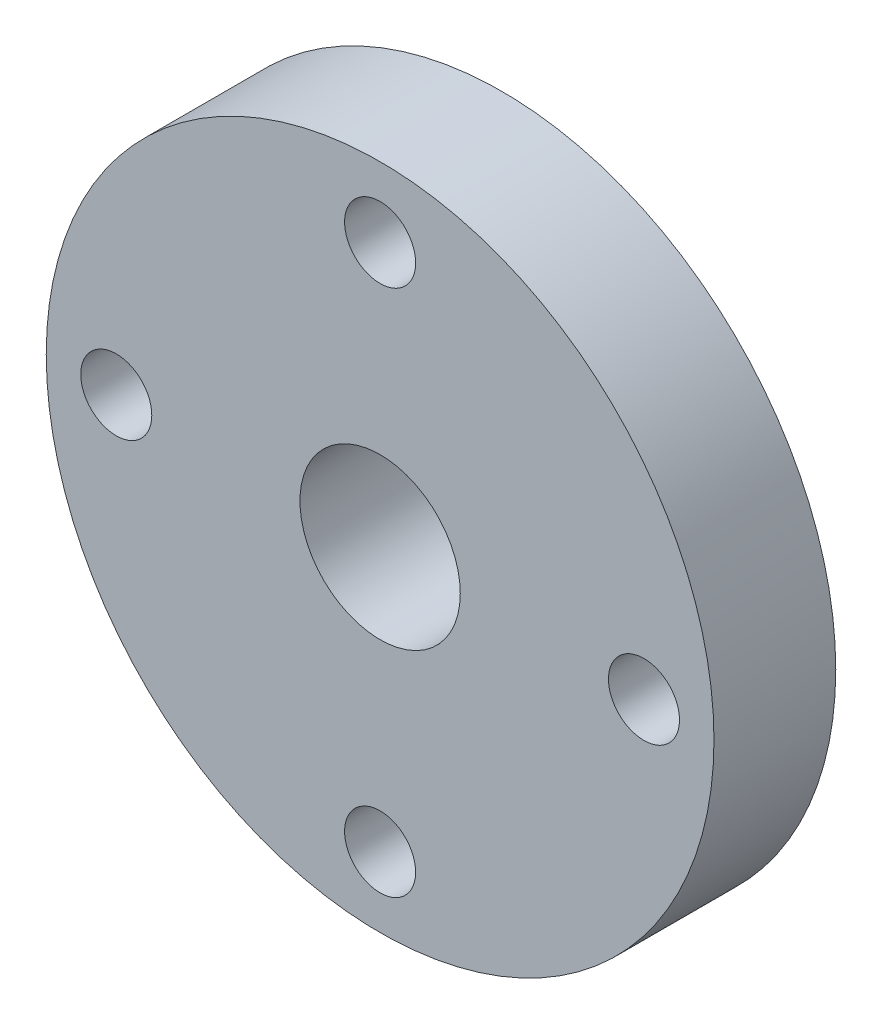
SolidWorks part; units mm, degrees
material "Balsa"
ref_plane "Front Plane" through (0, 0, 0) normal (0, 0, 1) x (1, 0, 0)
ref_plane "Top Plane" through (0, 0, 0) normal (0, 1, 0) x (1, 0, 0)
ref_plane "Right Plane" through (0, 0, 0) normal (1, 0, 0) x (0, 0, -1)
sketch "Sketch1" plane through (0, 0, 0) normal (0, 0, 1) x (1, 0, 0)
  circle A0 centre (0, 0) radius 16.4
  circle A1 centre (0, 0) radius 4
  circle A2 centre (0, 0) radius 13 construction
  circle A3 centre (0, 13) radius 1.8
  circle A4 centre (13, 0) radius 1.8
  circle A5 centre (0, -13) radius 1.8
  circle A6 centre (-13, 0) radius 1.8
  dimension "D1" = 32.8
  dimension "D2" = 26
  dimension "D3" = 8
  dimension "D4" = 3.6
extrude "Boss-Extrude1" add sketch "Sketch1" along normal blind 6
other "Move Face1" face at (1.8, 13, 6) face at (16.4, 0, 6) face at (4, 0, 6) face at (14.8, 0, 6) face at (1.8, -13, 6) face at (-11.2, 0, 6) parameters "D1"=0.05
